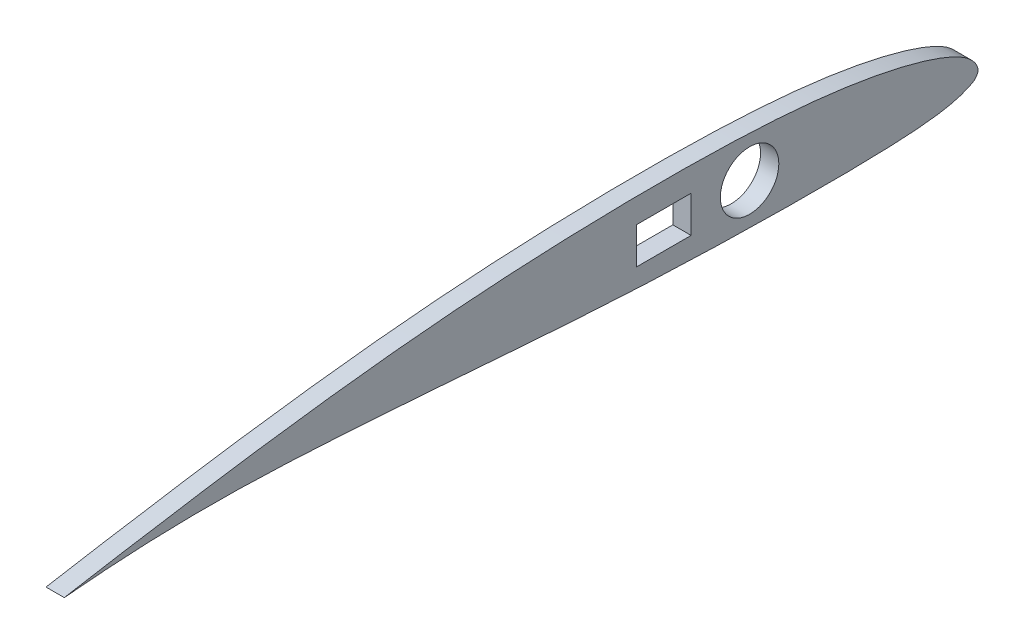
SolidWorks part; units mm, degrees
material "ABS generico"
ref_plane "Piano frontale" through (0, 0, 0) normal (0, 0, 1) x (1, 0, 0)
ref_plane "Piano superiore" through (0, 0, 0) normal (0, 1, 0) x (1, 0, 0)
ref_plane "Piano destro" through (0, 0, 0) normal (1, 0, 0) x (0, 0, -1)
curve "Curva1"
  spline degree 3 poles (0, 0.1724, 248.285) (0, -0.053, 250.4273) (0, 0.2462, 248.3284) (0, 0.5529, 246.6445) (0, 1.2459, 242.6221) (0, 2.0989, 237.7464) (0, 3.1818, 231.3634) (0, 4.2933, 223.9772) (0, 5.7312, 215.5604) (0, 7.1315, 206.3004) (0, 8.6324, 196.1631) (0, 10.1162, 185.3524) (0, 11.5493, 173.9891) (0, 12.8816, 162.1914) (0, 14.0593, 150.0724) (0, 15.0523, 137.7438) (0, 15.8256, 125.3116) (0, 16.3834, 112.8888) (0, 16.7267, 100.597) (0, 16.8648, 88.5669) (0, 16.792, 76.9314) (0, 16.4941, 65.8165) (0, 15.9609, 55.3329) (0, 15.1594, 45.573) (0, 14.0978, 36.6074) (0, 12.7884, 28.4972) (0, 11.2839, 21.2988) (0, 9.6413, 15.0749) (0, 7.9136, 9.8809) (0, 6.1182, 5.7699) (0, 4.2384, 2.7289) (0, 2.3057, 0.8126) (0, 0.7927, 0.0312) (0, -0.4105, -0.0213) (0, -1.7115, 0.4949) (0, -2.8658, 2.6253) (0, -4.0404, 5.6977) (0, -4.9287, 10.0719) (0, -5.5974, 15.6262) (0, -6.0122, 22.4122) (0, -6.265, 30.3619) (0, -6.3814, 39.3972) (0, -6.3554, 49.3987) (0, -6.2185, 60.2453) (0, -5.9476, 71.8018) (0, -5.5368, 83.9408) (0, -4.9386, 96.5461) (0, -4.1527, 109.5201) (0, -3.2196, 122.7671) (0, -2.1909, 136.1764) (0, -1.148, 149.6158) (0, -0.1602, 162.9314) (0, 0.706, 175.9537) (0, 1.3896, 188.4999) (0, 1.8332, 200.3712) (0, 1.9676, 211.3376) (0, 1.8232, 221.1842) (0, 1.4973, 229.6804) (0, 1.0741, 236.8065) (0, 0.6857, 242.1894) (0, 0.3087, 246.5181) (0, 0.1724, 248.285) (0, -0.053, 250.4273) (0, 0.2462, 248.3284) knots -0.014202 -0.006329 -0.001589 0 0.001576 0.006211 0.01368 0.023764 0.036307 0.051658 0.068045 0.086769 0.107053 0.128647 0.151303 0.174786 0.19886 0.223309 0.247929 0.272522 0.296848 0.320648 0.343669 0.365658 0.3864 0.405741 0.423561 0.439779 0.454311 0.467034 0.477831 0.486643 0.493542 0.498786 0.50271 0.50309 0.505896 0.510322 0.516831 0.525521 0.536535 0.549945 0.565696 0.583577 0.603379 0.624844 0.647727 0.671743 0.696673 0.722357 0.748609 0.77521 0.801891 0.828329 0.854175 0.879074 0.902636 0.924421 0.943939 0.960827 0.974827 0.985798 0.993671 0.998411 1 1.001576 1.006211 1.01368 periodic
sketch "Schizzo1" plane through (0, 0, 0) normal (1, 0, 0) x (0, 0, -1)
  line L0 (-250, 0) -> (0.0001, 0.0174) construction
  line L1 (0.0001, 0.0174) -> (-0.0034, 50.0174) construction
  line L2 (-62.4999, 16.3096) -> (-62.4999, -6.155) construction
  line L4 (-78.4999, 10.0773) -> (-93.4999, 10.0773)
  line L5 (-78.4999, 10.0773) -> (-78.4999, 0.0773)
  line L6 (-78.4999, 0.0773) -> (-93.4999, 0.0773)
  line L7 (-93.4999, 10.0773) -> (-93.4999, 0.0773)
  circle A0 centre (-62.4999, 5.0773) radius 8
  spline S0 degree 3 poles (-248.3284, 0.2462) (-250.4273, -0.053) (-248.285, 0.1724) (-246.5181, 0.3087) (-242.1894, 0.6857) (-236.8065, 1.0741) (-229.6804, 1.4973) (-221.1842, 1.8232) (-211.3376, 1.9676) (-200.3712, 1.8332) (-188.4999, 1.3896) (-175.9537, 0.706) (-162.9314, -0.1602) (-149.6158, -1.148) (-136.1764, -2.1909) (-122.7671, -3.2196) (-109.5201, -4.1527) (-96.5461, -4.9386) (-83.9408, -5.5368) (-71.8018, -5.9476) (-60.2453, -6.2185) (-49.3987, -6.3554) (-39.3972, -6.3814) (-30.3619, -6.265) (-22.4122, -6.0122) (-15.6262, -5.5974) (-10.0719, -4.9287) (-5.6977, -4.0404) (-2.6253, -2.8658) (-0.4949, -1.7115) (0.0213, -0.4105) (-0.0312, 0.7927) (-0.8126, 2.3057) (-2.7289, 4.2384) (-5.7699, 6.1182) (-9.8809, 7.9136) (-15.0749, 9.6413) (-21.2988, 11.2839) (-28.4972, 12.7884) (-36.6074, 14.0978) (-45.573, 15.1594) (-55.3329, 15.9609) (-65.8165, 16.4941) (-76.9314, 16.792) (-88.5669, 16.8648) (-100.597, 16.7267) (-112.8888, 16.3834) (-125.3116, 15.8256) (-137.7438, 15.0523) (-150.0724, 14.0593) (-162.1914, 12.8816) (-173.9891, 11.5493) (-185.3524, 10.1162) (-196.1631, 8.6324) (-206.3004, 7.1315) (-215.5604, 5.7312) (-223.9772, 4.2933) (-231.3634, 3.1818) (-237.7464, 2.0989) (-242.6221, 1.2459) (-246.6445, 0.5529) (-248.3284, 0.2462) (-250.4273, -0.053) (-248.285, 0.1724) knots -0.01368 -0.006211 -0.001576 0 0.001589 0.006329 0.014202 0.025173 0.039173 0.056061 0.075579 0.097364 0.120926 0.145825 0.171671 0.198109 0.22479 0.251391 0.277643 0.303327 0.328257 0.352273 0.375156 0.396621 0.416423 0.434304 0.450055 0.463465 0.474479 0.483169 0.489678 0.494104 0.49691 0.49729 0.501214 0.506458 0.513357 0.522169 0.532966 0.545689 0.560221 0.576439 0.594259 0.6136 0.634342 0.656331 0.679352 0.703152 0.727478 0.752071 0.776691 0.80114 0.825214 0.848697 0.871353 0.892947 0.913231 0.931955 0.948342 0.963693 0.976236 0.98632 0.993789 0.998424 1 1.001589 1.006329 1.014202 only from (-250, 0) to (-250, 0) construction
  spline S1 degree 3 poles (-248.3284, 0.2462) (-250.4273, -0.053) (-248.285, 0.1724) (-246.5181, 0.3087) (-242.1894, 0.6857) (-236.8065, 1.0741) (-229.6804, 1.4973) (-221.1842, 1.8232) (-211.3376, 1.9676) (-200.3712, 1.8332) (-188.4999, 1.3896) (-175.9537, 0.706) (-162.9314, -0.1602) (-149.6158, -1.148) (-136.1764, -2.1909) (-122.7671, -3.2196) (-109.5201, -4.1527) (-96.5461, -4.9386) (-83.9408, -5.5368) (-71.8018, -5.9476) (-60.2453, -6.2185) (-49.3987, -6.3554) (-39.3972, -6.3814) (-30.3619, -6.265) (-22.4122, -6.0122) (-15.6262, -5.5974) (-10.0719, -4.9287) (-5.6977, -4.0404) (-2.6253, -2.8658) (-0.4949, -1.7115) (0.0213, -0.4105) (-0.0312, 0.7927) (-0.8126, 2.3057) (-2.7289, 4.2384) (-5.7699, 6.1182) (-9.8809, 7.9136) (-15.0749, 9.6413) (-21.2988, 11.2839) (-28.4972, 12.7884) (-36.6074, 14.0978) (-45.573, 15.1594) (-55.3329, 15.9609) (-65.8165, 16.4941) (-76.9314, 16.792) (-88.5669, 16.8648) (-100.597, 16.7267) (-112.8888, 16.3834) (-125.3116, 15.8256) (-137.7438, 15.0523) (-150.0724, 14.0593) (-162.1914, 12.8816) (-173.9891, 11.5493) (-185.3524, 10.1162) (-196.1631, 8.6324) (-206.3004, 7.1315) (-215.5604, 5.7312) (-223.9772, 4.2933) (-231.3634, 3.1818) (-237.7464, 2.0989) (-242.6221, 1.2459) (-246.6445, 0.5529) (-248.3284, 0.2462) (-250.4273, -0.053) (-248.285, 0.1724) knots -0.01368 -0.006211 -0.001576 0 0.001589 0.006329 0.014202 0.025173 0.039173 0.056061 0.075579 0.097364 0.120926 0.145825 0.171671 0.198109 0.22479 0.251391 0.277643 0.303327 0.328257 0.352273 0.375156 0.396621 0.416423 0.434304 0.450055 0.463465 0.474479 0.483169 0.489678 0.494104 0.49691 0.49729 0.501214 0.506458 0.513357 0.522169 0.532966 0.545689 0.560221 0.576439 0.594259 0.6136 0.634342 0.656331 0.679352 0.703152 0.727478 0.752071 0.776691 0.80114 0.825214 0.848697 0.871353 0.892947 0.913231 0.931955 0.948342 0.963693 0.976236 0.98632 0.993789 0.998424 1 1.001589 1.006329 1.014202 only from (-250, 0) to (-250, 0)
  point P11 (-78.4999, 5.0773)
  dimension "D3" = 16
  dimension "D1" = 50
  dimension "D2" = 62.5
  dimension "D4" = 15
  dimension "D5" = 10
  dimension "D6" = 16
extrude "CorpoFoam" add sketch "Schizzo1" along normal blind 5
